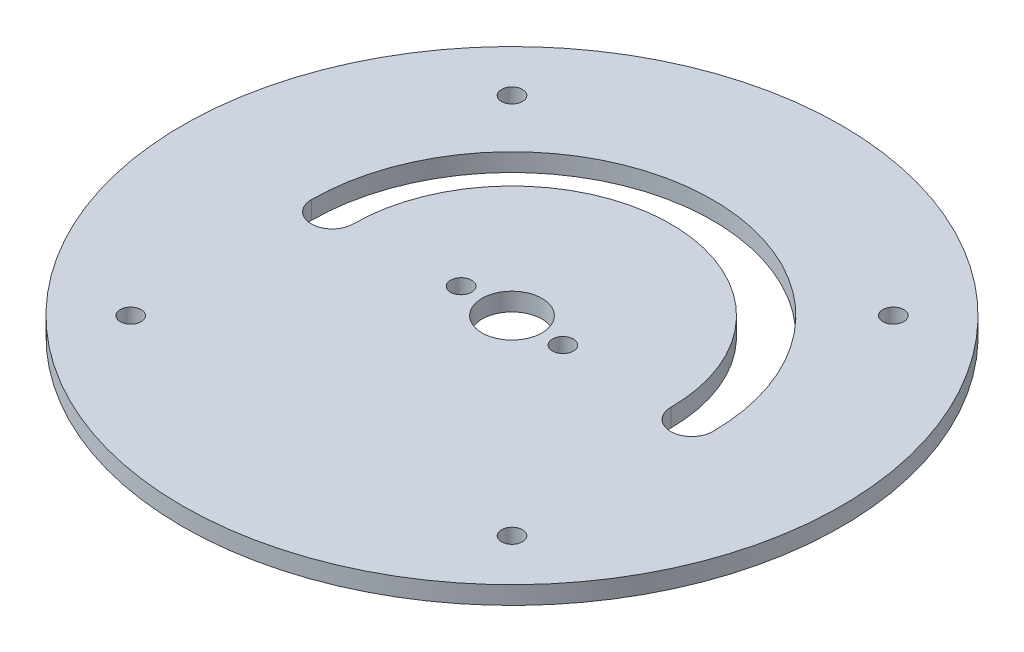
SolidWorks part; units mm, degrees
ref_plane "Front Plane" through (0, 0, 0) normal (0, 0, 1) x (1, 0, 0)
ref_plane "Top Plane" through (0, 0, 0) normal (0, 1, 0) x (1, 0, 0)
ref_plane "Right Plane" through (0, 0, 0) normal (1, 0, 0) x (0, 0, -1)
sketch "Sketch1" plane through (0, 0, 0) normal (0, 1, 0) x (1, 0, 0)
  line L0 (-1432.9192, 0) -> (70213.0409, 0) construction
  line L1 (0, -1432.9192) -> (0, 70213.0409) construction
  circle A0 centre (0, 0) radius 5
  circle A2 centre (8.5, 0) radius 1.75
  circle A3 centre (-8.5, 0) radius 1.75
  circle A4 centre (-31.8198, 31.8198) radius 1.75
  circle A5 centre (31.8198, 31.8198) radius 1.75
  circle A6 centre (31.8198, -31.8198) radius 1.75
  circle A7 centre (-31.8198, -31.8198) radius 1.75
  circle A12 centre (0, 0) radius 55
  arc A13 (30, 0) -> (-30, 0) centre (0, 0) ccw construction
  arc A14 (33.5, 0) -> (-33.5, 0) centre (0, 0) ccw
  arc A15 (26.5, 0) -> (-26.5, 0) centre (0, 0) ccw
  arc A16 (26.5, 0) -> (33.5, 0) centre (30, 0) ccw
  arc A17 (-33.5, 0) -> (-26.5, 0) centre (-30, 0) ccw
  point P8 (0, 30)
  point P26 (0, 0)
  dimension "D1" = 10
  dimension "D2" = 8.5
  dimension "D3" = 3.5
  dimension "D8" = 3.5
  dimension "D4" = 110
  dimension "D6" = 30
  dimension "D7" = 7
  dimension "D5" = 45
  dimension "D11" = 4
extrude "Boss-Extrude1" add sketch "Sketch1" along normal blind 3
